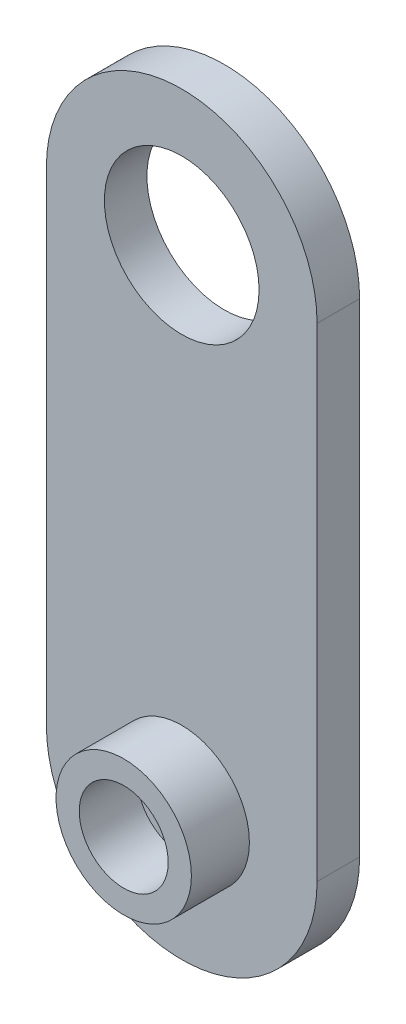
SolidWorks part; units mm, degrees
ref_plane "Alzado" through (0, 0, 0) normal (0, 0, 1) x (1, 0, 0)
ref_plane "Planta" through (0, 0, 0) normal (0, 1, 0) x (1, 0, 0)
ref_plane "Vista lateral" through (0, 0, 0) normal (1, 0, 0) x (0, 0, -1)
sketch "Croquis1" plane through (0, 0, 0) normal (0, 0, 1) x (1, 0, 0)
  line L0 (0, 0) -> (0, 25) construction
  line L1 (-7, 25) -> (-7, 0)
  line L2 (7, 25) -> (7, 0)
  arc A0 (-7, 0) -> (7, 0) centre (0, 0) ccw
  arc A1 (7, 25) -> (-7, 25) centre (0, 25) ccw
  circle A2 centre (0, 0) radius 1.1
  arc A3 (4, 25) -> (-4, 25) centre (0, 25) ccw
  arc A5 (4, 25) -> (-4, 25) centre (0, 25) cw
  dimension "D1" = 14
  dimension "D2" = 14
  dimension "D4" = 2.2
  dimension "D5" = 4
  dimension "D3" = 25
extrude "Saliente-Extruir1" add sketch "Croquis1" along normal blind 2.2
sketch "Croquis2" plane through (0, 0, 2.2) normal (0, 0, 1) x (1, 0, 0)
  circle A0 centre (0, 0) radius 3.5
  circle A1 centre (0, 0) radius 2.3
  dimension "D1" = 1.2
  dimension "D2" = 7
extrude "Saliente-Extruir2" add sketch "Croquis2" along normal blind 3
sketch "Croquis3" plane through (0, 0, 0) normal (0, 0, -1) x (-1, 0, 0)
  circle A0 centre (0, 0) radius 2.25
  dimension "D1" = 4.5
extrude "Cortar-Extruir1" cut sketch "Croquis3" against normal blind 1
